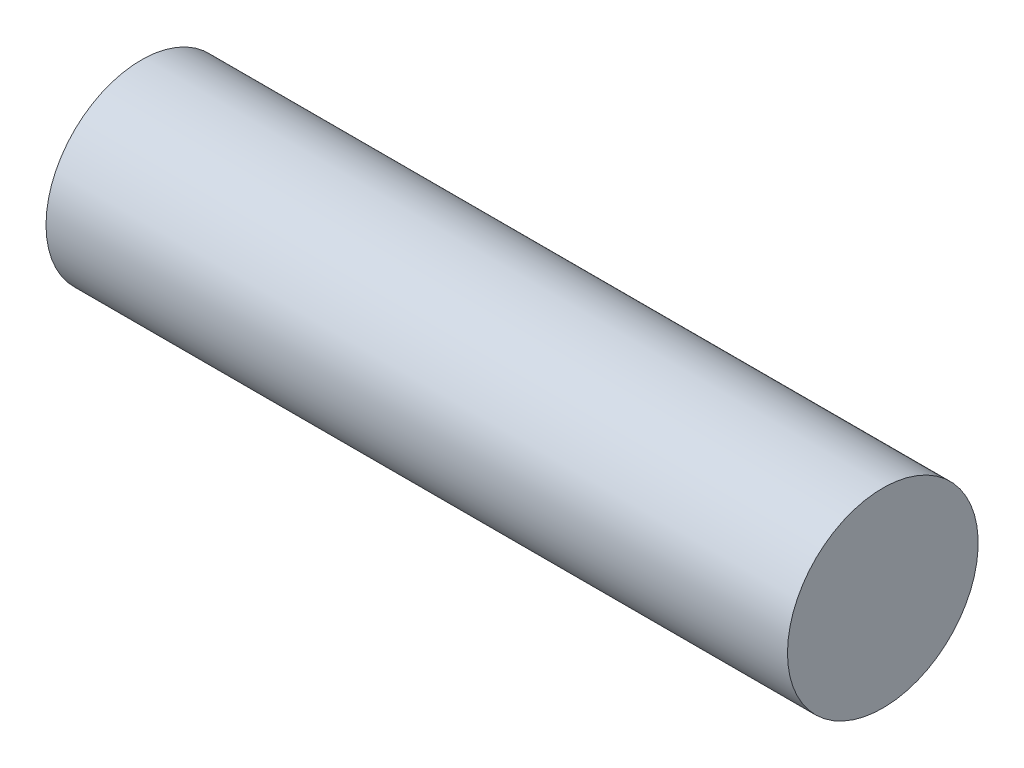
SolidWorks part; units mm, degrees
material "Rocket Motor"
ref_plane "Front Plane" through (0, 0, 0) normal (0, 0, 1) x (1, 0, 0)
ref_plane "Top Plane" through (0, 0, 0) normal (0, 1, 0) x (1, 0, 0)
ref_plane "Right Plane" through (0, 0, 0) normal (1, 0, 0) x (0, 0, -1)
sketch "Sketch1" plane through (0, 0, 0) normal (0, 0, 1) x (1, 0, 0)
  line L0 (0, 0) -> (53395.0263, 0) construction
  line L2 (0, 0) -> (-70, 0)
  line L3 (0, 0) -> (0, 9)
  line L4 (0, 9) -> (-70, 9)
  line L5 (-70, 0) -> (-70, 9)
  dimension "D1" = 70
  dimension "D2" = 9
revolve "Revolve1" add sketch "Sketch1" angle 360 about L0
